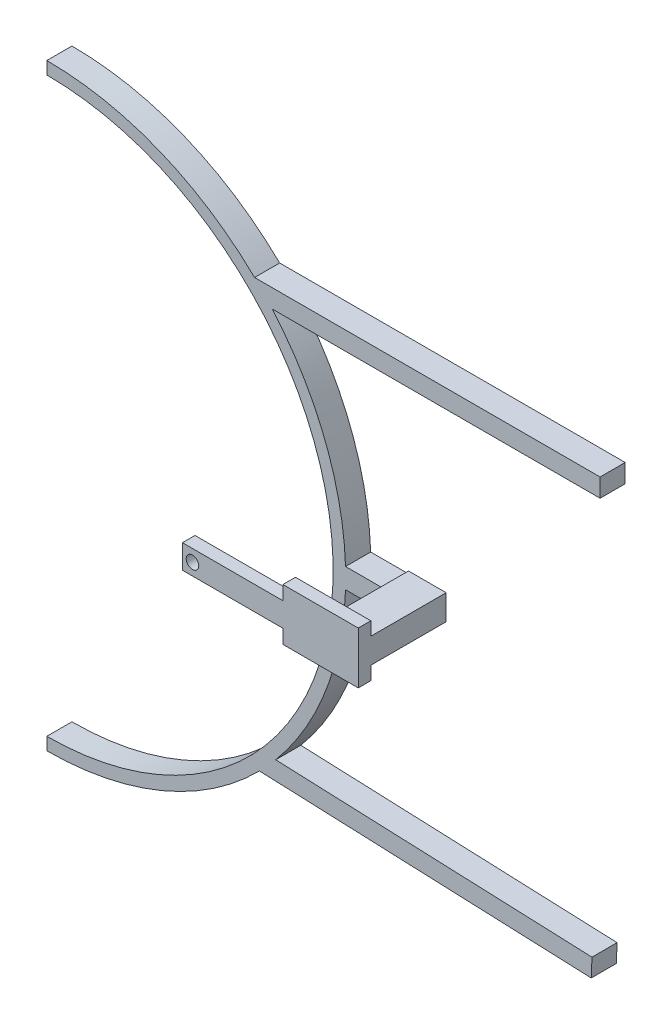
SolidWorks part; units mm, degrees
ref_plane "Front Plane" through (0, 0, 0) normal (0, 0, 1) x (1, 0, 0)
ref_plane "Top Plane" through (0, 0, 0) normal (0, 1, 0) x (1, 0, 0)
ref_plane "Right Plane" through (0, 0, 0) normal (1, 0, 0) x (0, 0, -1)
sketch "Sketch1" plane through (0, 0, 0) normal (0, 0, 1) x (1, 0, 0)
  line L0 (-15, 4.7489) -> (-15, 10.3276)
  line L1 (15, -10.3276) -> (-15, -10.3276)
  line L2 (15, -10.3276) -> (15, 10.3276)
  line L3 (15, 10.3276) -> (-15, 10.3276)
  line L5 (15, -10.3276) -> (-15, 10.3276) construction
  line L6 (15, 10.3276) -> (-15, -10.3276) construction
  line L7 (-15, -4.7489) -> (-55, -4.7489)
  line L9 (-15, 4.7489) -> (-55, 4.7489)
  line L10 (-55, -4.7489) -> (-55, 4.7489)
  line L11 (-15, -4.7489) -> (-55, 4.7489) construction
  line L12 (-15, 4.7489) -> (-55, -4.7489) construction
  line L13 (-15, -4.7489) -> (-15, -10.3276)
  circle A0 centre (-51, 0) radius 2.5
  point P0 (0, 0)
  point P6 (-35, 0)
  point P15 (-55, 0)
  dimension "D1" = 5
  dimension "D2" = 30
  dimension "D3" = 40
  dimension "D4" = 4
extrude "Boss-Extrude1" add sketch "Sketch1" along normal blind 5
sketch "Sketch2" plane through (0, 0, 0) normal (0, 0, -1) x (-1, 0, 0)
  line L0 (-15, -10.3276) -> (-15, 10.3276) construction
  line L1 (-15, 5) -> (0, 5)
  line L2 (-15, 5) -> (-15, -5)
  line L3 (-15, -5) -> (0, -5)
  line L4 (0, 5) -> (0, -5)
  line L5 (-15, 5) -> (0, -5) construction
  line L6 (-15, -5) -> (0, 5) construction
  point P0 (-7.5, 0)
  dimension "D1" = 10
  dimension "D2" = 15
extrude "Boss-Extrude2" add sketch "Sketch2" along normal blind 30
sketch "Sketch3" plane through (0, 0, 0) normal (-1, 0, 0) x (0, 0, 1)
  line L0 (-30, -5) -> (-30, 5) construction
  line L1 (-30, 4) -> (-20, 4)
  line L2 (-30, 4) -> (-30, -4)
  line L3 (-30, -4) -> (-20, -4)
  line L4 (-20, 4) -> (-20, -4)
  line L5 (-30, 4) -> (-20, -4) construction
  line L6 (-30, -4) -> (-20, 4) construction
  point P0 (-25, 0)
  dimension "D1" = 10
  dimension "D2" = 8
extrude "Boss-Extrude3" add sketch "Sketch3" along normal blind 20
sketch "Sketch5" plane through (0, 0, -30) normal (0, 0, -1) x (-1, 0, 0)
  line L1 (134, -114) -> (134, -119)
  line L3 (134, 114) -> (134, 119)
  arc A0 (134, 114) -> (134, -114) centre (134, 0) ccw
  arc A1 (134, 119) -> (134, -119) centre (134, 0) ccw
  dimension "D3" = 114
  dimension "D1" = 5
extrude "Boss-Extrude5" add sketch "Sketch5" against normal blind 10
sketch "Sketch6" plane through (0, 0, -30) normal (0, 0, -1) x (-1, 0, 0)
  line L0 (51.2806, 85.5482) -> (-86.273, 85.5482)
  line L1 (-86.273, 85.5482) -> (-86.273, 78.2028)
  line L2 (-86.273, 78.2028) -> (44.3043, 78.2028)
  line L3 (0, 0) -> (74.258, 1.5) construction
  line L4 (-34.5077, 1.5) -> (304.4923, 1.5) construction
  line L5 (-83.0446, -81.623) -> (47.4262, -76.3498)
  line L6 (-82.748, -88.9624) -> (-83.0446, -81.623)
  line L7 (54.6935, -83.4076) -> (-82.748, -88.9624)
  arc A0 (134, 119) -> (15.0672, 4) centre (134, 0) ccw construction
  arc A1 (44.3043, 78.2028) -> (51.2806, 85.5482) centre (134, 0) cw
  arc A2 (47.4262, -76.3498) -> (54.6935, -83.4076) centre (133.8907, 5.4113) ccw
extrude "Boss-Extrude6" add sketch "Sketch6" against normal blind 10
